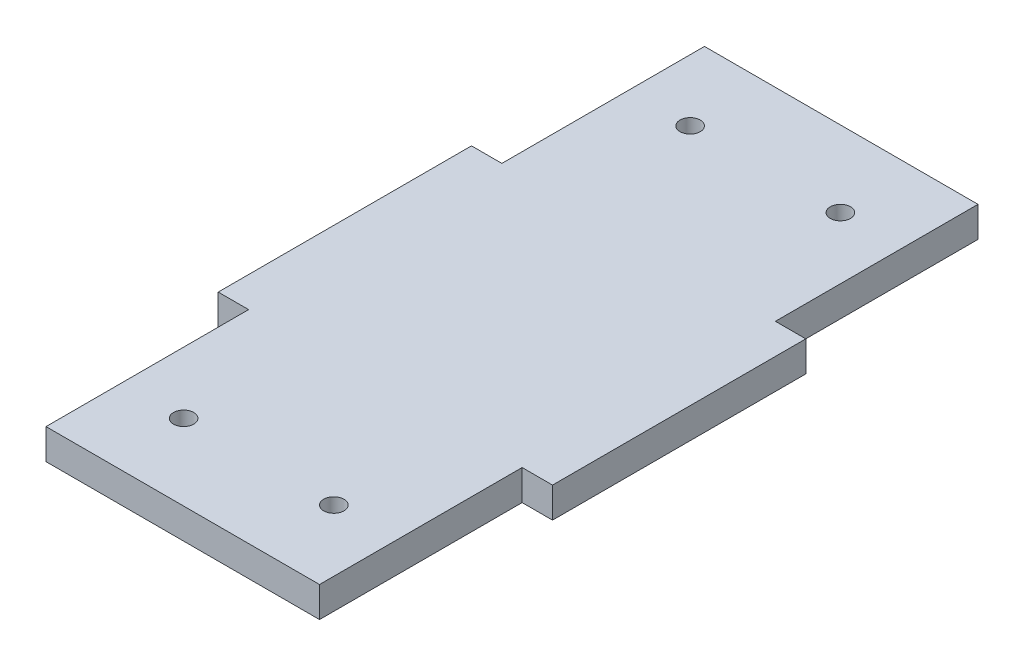
SolidWorks part; units mm, degrees
ref_plane "前视" through (0, 0, 0) normal (0, 0, 1) x (1, 0, 0)
ref_plane "上视" through (0, 0, 0) normal (0, 1, 0) x (1, 0, 0)
ref_plane "右视" through (0, 0, 0) normal (1, 0, 0) x (0, 0, -1)
sketch "Sketch1" plane through (0, 0, 0) normal (0, 1, 0) x (1, 0, 0)
  line L0 (4.3716, 58.7932) -> (4.3716, 18.7932)
  line L1 (-49.6284, 58.7932) -> (10.3716, 58.7932)
  line L2 (-49.6284, 58.7932) -> (-49.6284, 18.7932)
  line L3 (-49.6284, -71.2068) -> (10.3716, -71.2068)
  line L4 (10.3716, 58.7932) -> (10.3716, -71.2068)
  line L5 (-55.6284, 18.7932) -> (-49.6284, 18.7932)
  line L6 (4.3716, -31.2068) -> (4.3716, -71.2068)
  line L7 (-55.6284, -31.2068) -> (-49.6284, -31.2068)
  line L8 (-55.6284, 18.7932) -> (-55.6284, -31.2068)
  line L9 (4.3716, -31.2068) -> (10.3716, -31.2068)
  line L10 (4.3716, 18.7932) -> (10.3716, 18.7932)
  line L11 (-49.6284, -31.2068) -> (-49.6284, -71.2068)
  dimension "D1" = 130
  dimension "D2" = 60
  dimension "D3" = 40
  dimension "D4" = 40
  dimension "D5" = 6
  dimension "D6" = 6
extrude "Boss-Extrude1" add sketch "Sketch1" along normal blind 6 contours L6 L7 L4 L5 L0 L1 L2 L3
sketch "Sketch2" plane through (0, 6, 0) normal (0, 1, 0) x (1, 0, 0)
  line L1 (-49.6284, -71.2068) -> (4.3716, -71.2068) construction
  line L2 (-49.6284, 58.7932) -> (4.3716, 58.7932) construction
  line L3 (4.3716, 58.7932) -> (4.3716, 18.7932) construction
  line L4 (4.3716, -31.2068) -> (4.3716, -71.2068) construction
  line L5 (-49.6284, -71.2068) -> (4.3716, -71.2068) construction
  line L6 (-49.6284, -31.2068) -> (-49.6284, -71.2068) construction
  line L7 (-49.6284, 58.7932) -> (-49.6284, 18.7932) construction
  circle A0 centre (-7.7984, -56.2068) radius 2
  circle A1 centre (-7.7984, 43.7932) radius 2
  circle A2 centre (-37.4584, 43.7932) radius 2
  circle A3 centre (-37.4584, -56.2068) radius 2
  dimension "D1" = 12.17
  dimension "D2" = 12.17
  dimension "D5" = 4
  dimension "D6" = 4
  dimension "D7" = 4
  dimension "D8" = 4
  dimension "D10" = 12.17
  dimension "D11" = 12.17
  dimension "D12" = 15
  dimension "D3" = 15
  dimension "D4" = 15
  dimension "D9" = 15
extrude "Cut-Extrude1" cut sketch "Sketch2" against normal through all
